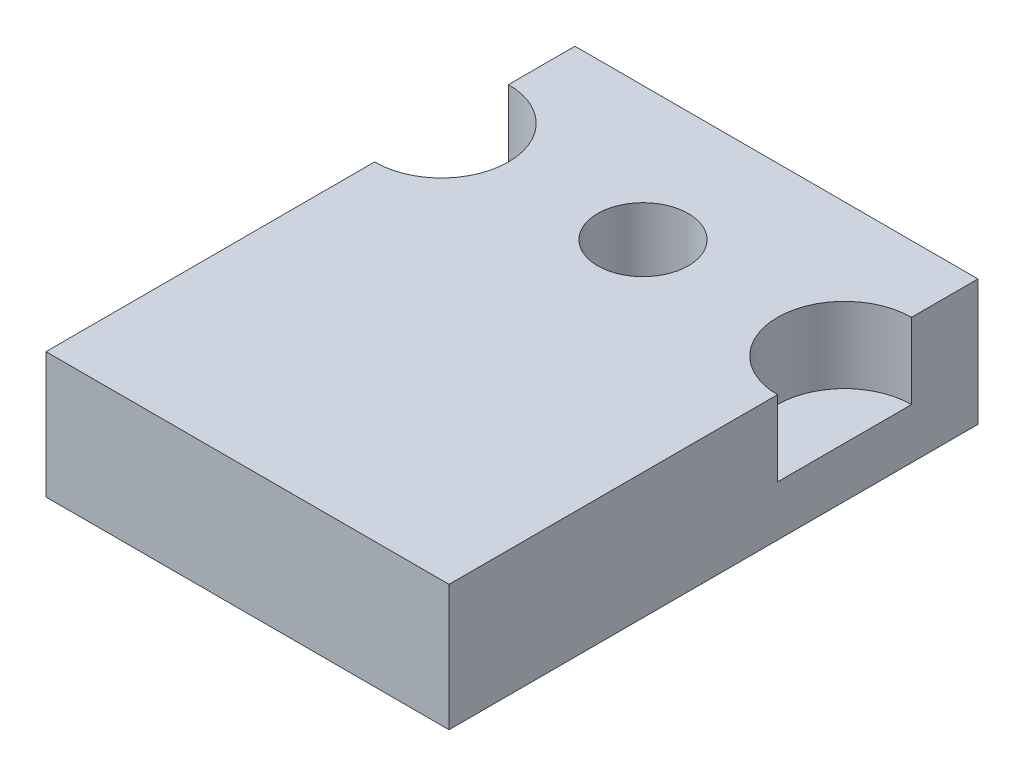
SolidWorks part; units mm, degrees
material "ABS"
ref_plane "Front Plane" through (0, 0, 0) normal (0, 0, 1) x (1, 0, 0)
ref_plane "Top Plane" through (0, 0, 0) normal (0, 1, 0) x (1, 0, 0)
ref_plane "Right Plane" through (0, 0, 0) normal (1, 0, 0) x (0, 0, -1)
sketch "Sketch1" plane through (0, 0, 0) normal (0, 1, 0) x (1, 0, 0)
  line L0 (0, 10.5) -> (0, 7) construction
  line L1 (-8, -10.5) -> (8, -10.5)
  line L2 (-8, -10.5) -> (-8, 10.5)
  line L3 (-8, 10.5) -> (8, 10.5)
  line L4 (8, -10.5) -> (8, 10.5)
  line L5 (-8, -10.5) -> (8, 10.5) construction
  line L6 (-8, 10.5) -> (8, -10.5) construction
  line L7 (0, 7) -> (0, 5.2) construction
  circle A0 centre (0, 5.2) radius 1.8
  point P0 (0, 0)
  dimension "D1" = 16
  dimension "D2" = 21
  dimension "D3" = 3.5
  dimension "D4" = 1.8
extrude "Boss-Extrude2" add sketch "Sketch1" along normal blind 5
sketch "Sketch2" plane through (0, 5, 0) normal (0, 1, 0) x (1, 0, 0)
  line L0 (-8, 10.5) -> (-8, 7.86) construction
  line L1 (-8, 10.5) -> (-8, -10.5) construction
  line L2 (-8, 7.86) -> (-8, 5.2) construction
  line L3 (8, 10.5) -> (8, 7.86) construction
  line L4 (8, -10.5) -> (8, 10.5) construction
  line L5 (8, 7.86) -> (8, 5.2) construction
  circle A0 centre (-8, 5.2) radius 2.66
  circle A1 centre (8, 5.2) radius 2.66
  dimension "D1" = 2.64
  dimension "D2" = 2.66
  dimension "D3" = 2.64
  dimension "D4" = 2.66
extrude "Cut-Extrude1" cut sketch "Sketch2" against normal blind 3
